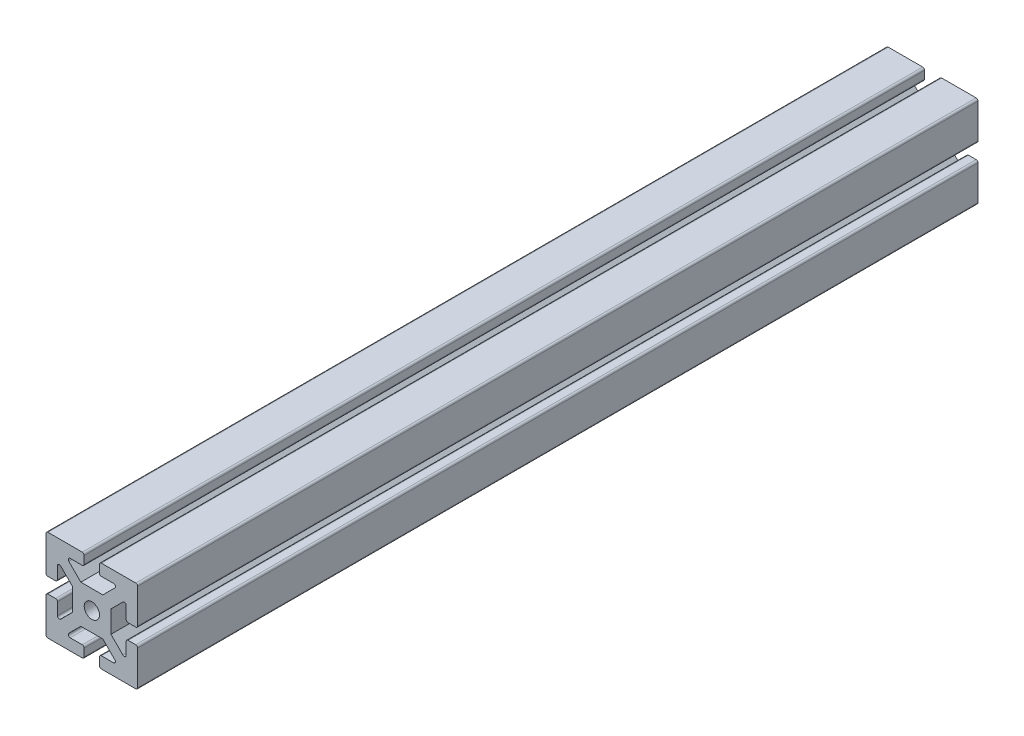
SolidWorks part; units mm, degrees
ref_plane "Płaszczyzna przednia" through (0, 0, 0) normal (0, 0, 1) x (1, 0, 0)
ref_plane "Płaszczyzna górna" through (0, 0, 0) normal (0, 1, 0) x (1, 0, 0)
ref_plane "Płaszczyzna prawa" through (0, 0, 0) normal (1, 0, 0) x (0, 0, -1)
sketch "Szkic1" plane through (0, 0, 0) normal (0, 0, 1) x (1, 0, 0)
  line L0 (-1.4393, 2.5) -> (1.4393, 2.5)
  line L1 (1.4393, 2.5) -> (3.0126, 4.0732)
  line L2 (2.8358, 4.5) -> (1.25, 4.5)
  line L3 (1, 4.75) -> (1, 5.75)
  line L4 (1.25, 6) -> (5.75, 6)
  line L5 (6, 5.75) -> (6, 1.25)
  line L6 (4.75, 1) -> (5.75, 1)
  line L7 (4.5, 1.25) -> (4.5, 2.8358)
  line L8 (4.0732, 3.0126) -> (2.5, 1.4393)
  line L9 (0, 0) -> (0, 2.5) construction
  line L10 (2.5, 1.4393) -> (2.5, -1.4393)
  line L11 (2.5, -1.4393) -> (4.0732, -3.0126)
  line L12 (4.5, -2.8358) -> (4.5, -1.25)
  line L13 (4.75, -1) -> (5.75, -1)
  line L14 (6, -1.25) -> (6, -5.75)
  line L15 (5.75, -6) -> (1.25, -6)
  line L16 (1, -4.75) -> (1, -5.75)
  line L17 (1.25, -4.5) -> (2.8358, -4.5)
  line L18 (3.0126, -4.0732) -> (1.4393, -2.5)
  line L19 (1.4393, -2.5) -> (-1.4393, -2.5)
  line L20 (-1.4393, -2.5) -> (-3.0126, -4.0732)
  line L21 (-2.8358, -4.5) -> (-1.25, -4.5)
  line L22 (-1, -4.75) -> (-1, -5.75)
  line L23 (-1.25, -6) -> (-5.75, -6)
  line L24 (-6, -5.75) -> (-6, -1.25)
  line L25 (-4.75, -1) -> (-5.75, -1)
  line L26 (-4.5, -1.25) -> (-4.5, -2.8358)
  line L27 (-4.0732, -3.0126) -> (-2.5, -1.4393)
  line L28 (-2.5, -1.4393) -> (-2.5, 1.4393)
  line L29 (-2.5, 1.4393) -> (-4.0732, 3.0126)
  line L30 (-4.5, 2.8358) -> (-4.5, 1.25)
  line L31 (-4.75, 1) -> (-5.75, 1)
  line L32 (-6, 1.25) -> (-6, 5.75)
  line L33 (-5.75, 6) -> (-1.25, 6)
  line L34 (-1, 4.75) -> (-1, 5.75)
  line L35 (-1.25, 4.5) -> (-2.8358, 4.5)
  line L36 (-3.0126, 4.0732) -> (-1.4393, 2.5)
  circle A0 centre (0, 0) radius 1
  arc A1 (3.0126, 4.0732) -> (2.8358, 4.5) centre (2.8358, 4.25) ccw
  arc A2 (1.25, 4.5) -> (1, 4.75) centre (1.25, 4.75) cw
  arc A3 (1, 5.75) -> (1.25, 6) centre (1.25, 5.75) cw
  arc A4 (5.75, 6) -> (6, 5.75) centre (5.75, 5.75) cw
  arc A5 (4.75, 1) -> (4.5, 1.25) centre (4.75, 1.25) cw
  arc A6 (5.75, 1) -> (6, 1.25) centre (5.75, 1.25) ccw
  arc A7 (4.0732, 3.0126) -> (4.5, 2.8358) centre (4.25, 2.8358) cw
  arc A8 (4.0732, -3.0126) -> (4.5, -2.8358) centre (4.25, -2.8358) ccw
  arc A9 (4.5, -1.25) -> (4.75, -1) centre (4.75, -1.25) cw
  arc A10 (5.75, -1) -> (6, -1.25) centre (5.75, -1.25) cw
  arc A11 (6, -5.75) -> (5.75, -6) centre (5.75, -5.75) cw
  arc A12 (1, -5.75) -> (1.25, -6) centre (1.25, -5.75) ccw
  arc A13 (1, -4.75) -> (1.25, -4.5) centre (1.25, -4.75) cw
  arc A14 (3.0126, -4.0732) -> (2.8358, -4.5) centre (2.8358, -4.25) cw
  arc A15 (-3.0126, -4.0732) -> (-2.8358, -4.5) centre (-2.8358, -4.25) ccw
  arc A16 (-1.25, -4.5) -> (-1, -4.75) centre (-1.25, -4.75) cw
  arc A17 (-1, -5.75) -> (-1.25, -6) centre (-1.25, -5.75) cw
  arc A18 (-5.75, -6) -> (-6, -5.75) centre (-5.75, -5.75) cw
  arc A19 (-5.75, -1) -> (-6, -1.25) centre (-5.75, -1.25) ccw
  arc A20 (-4.75, -1) -> (-4.5, -1.25) centre (-4.75, -1.25) cw
  arc A21 (-4.0732, -3.0126) -> (-4.5, -2.8358) centre (-4.25, -2.8358) cw
  arc A22 (-4.0732, 3.0126) -> (-4.5, 2.8358) centre (-4.25, 2.8358) ccw
  arc A23 (-4.5, 1.25) -> (-4.75, 1) centre (-4.75, 1.25) cw
  arc A24 (-5.75, 1) -> (-6, 1.25) centre (-5.75, 1.25) cw
  arc A25 (-6, 5.75) -> (-5.75, 6) centre (-5.75, 5.75) cw
  arc A26 (-1, 5.75) -> (-1.25, 6) centre (-1.25, 5.75) ccw
  arc A27 (-1, 4.75) -> (-1.25, 4.5) centre (-1.25, 4.75) cw
  arc A28 (-3.0126, 4.0732) -> (-2.8358, 4.5) centre (-2.8358, 4.25) cw
  point P26 (0, 0)
  point P28 (0, 0)
  point P103 (0, 0)
  dimension "D1" = 2
  dimension "D6" = 0.25
  dimension "D7" = 0.25
  dimension "D8" = 0.25
  dimension "D9" = 0.25
  dimension "D10" = 0.25
  dimension "D11" = 0.25
  dimension "D12" = 0.25
  dimension "D2" = 2.5
  dimension "D3" = 1.5
  dimension "D4" = 1.5
  dimension "D5" = 2
  dimension "D14" = 2
  dimension "D13" = 4
extrude "Dodanie-wyciągnięcie1" add sketch "Szkic1" against normal blind 110
